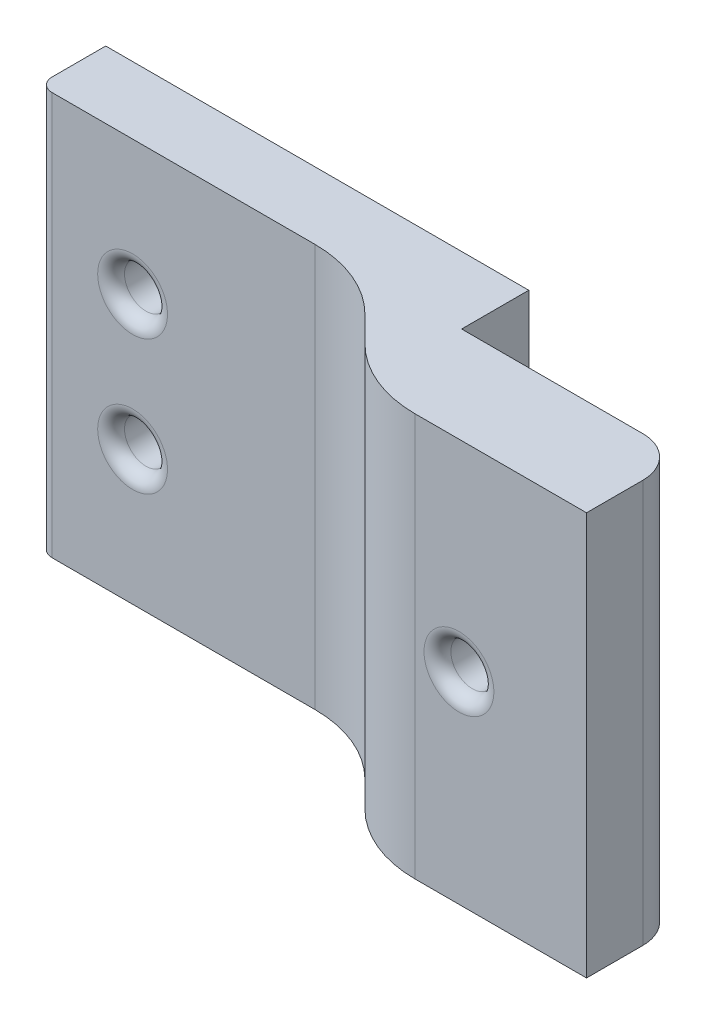
SolidWorks part; units mm, degrees
ref_plane "Front Plane" through (0, 0, 0) normal (0, 0, 1) x (1, 0, 0)
ref_plane "Top Plane" through (0, 0, 0) normal (0, 1, 0) x (1, 0, 0)
ref_plane "Right Plane" through (0, 0, 0) normal (1, 0, 0) x (0, 0, -1)
sketch "Sketch1" plane through (0, 0, 0) normal (0, 1, 0) x (1, 0, 0)
  line L0 (-5.879, -9.0924) -> (-13.079, -1.8924)
  line L1 (-5.879, -1.8924) -> (10.621, -1.8924)
  line L3 (-5.879, -9.0924) -> (10.621, -9.0924)
  line L4 (10.621, -1.8924) -> (10.621, -9.0924)
  line L5 (-37.379, -1.8924) -> (-37.379, 3.1076)
  line L7 (-37.379, -1.8924) -> (-13.079, -1.8924)
  line L8 (-5.879, 3.1076) -> (-5.879, -1.8924)
  line L9 (-5.879, 3.1076) -> (-37.379, 3.1076)
extrude "Boss-Extrude1" add sketch "Sketch1" along normal blind 30
sketch "Sketch2" plane through (0, 0, 9.0924) normal (0, 0, 1) x (1, 0, 0)
  circle A0 centre (1.121, 15) radius 1.6
extrude "Cut-Extrude1" cut sketch "Sketch2" against normal up to surface (7.2 mm away) up to face at (2.371, 15, 1.8924)
sketch "Sketch3" plane through (0, 0, 1.8924) normal (0, 0, 1) x (1, 0, 0)
  line L2 (-30.379, 30) -> (-30.379, 20)
  line L3 (-37.379, 30) -> (-13.079, 30) construction
  line L4 (-30.379, 0) -> (-30.379, 10)
  line L5 (-37.379, 0) -> (-13.079, 0) construction
  circle A0 centre (-30.379, 20) radius 1.6
  circle A1 centre (-30.379, 10) radius 1.6
extrude "Cut-Extrude2" cut sketch "Sketch3" against normal up to surface (5 mm away) up to face at (-21.629, 15, -3.1076)
fillet "Fillet1" radius 1 6 edges at (2.721, 15, 1.8924) (2.721, 15, 9.0924) (-28.779, 10, 1.8924) (-28.779, 20, 1.8924) (-28.779, 20, -3.1076) (-28.779, 10, -3.1076)
fillet "Fillet2" radius 3 1 edges at (10.621, 15, 1.8924)
fillet "Fillet3" radius 9 2 edges at (-13.079, 15, 1.8924) (-5.879, 15, 9.0924)
fillet "Fillet4" radius 1 1 edges at (-37.379, 15, 1.8924)
